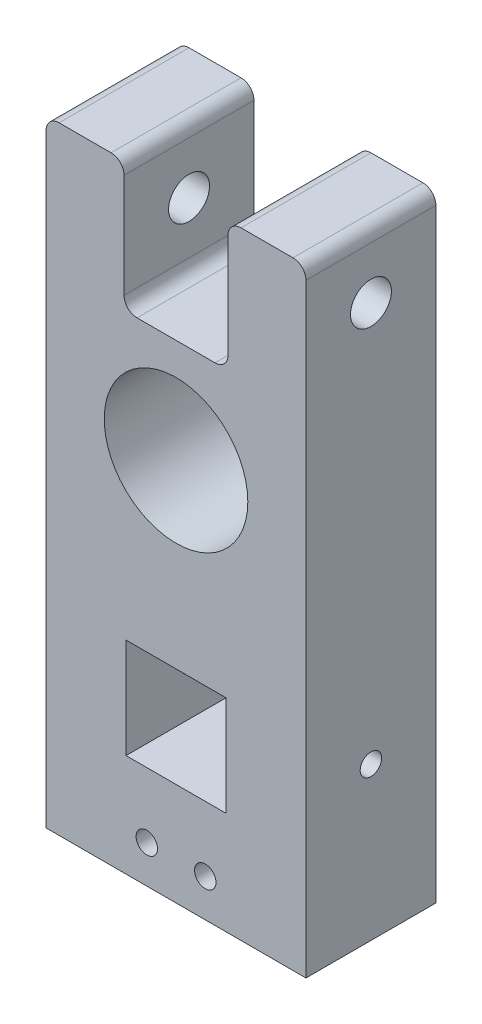
SolidWorks part; units mm, degrees
ref_plane "前视基准面" through (0, 0, 0) normal (0, 0, 1) x (1, 0, 0)
ref_plane "上视基准面" through (0, 0, 0) normal (0, 1, 0) x (1, 0, 0)
ref_plane "右视基准面" through (0, 0, 0) normal (1, 0, 0) x (0, 0, -1)
sketch "草图1" plane through (0, 0, 0) normal (0, 0, 1) x (1, 0, 0)
  line L1 (-20, -48.45) -> (20, -48.45)
  line L2 (-20, -48.45) -> (-20, 46.55)
  line L3 (-20, 46.55) -> (20, 46.55)
  line L4 (20, -48.45) -> (20, 46.55)
  line L5 (-20, -48.45) -> (20, 46.55) construction
  line L6 (-20, 46.55) -> (20, -48.45) construction
  point P0 (0, -0.95)
  dimension "D1" = 40
  dimension "D2" = 95
extrude "凸台-拉伸1" add sketch "草图1" along normal blind 20
sketch "草图2" plane through (20, 0, 0) normal (1, 0, 0) x (0, 0, -1)
  line L0 (-10, 46.55) -> (-10, -48.45) construction
  line L1 (-20, 46.55) -> (0, 46.55) construction
  line L2 (-20, -48.45) -> (0, -48.45) construction
  circle A0 centre (-10, 36.55) radius 3.15
  dimension "D1" = 6.3
  dimension "D2" = 10
extrude "切除-拉伸1" cut sketch "草图2" against normal blind 500
sketch "草图4" plane through (0, 0, 20) normal (0, 0, 1) x (1, 0, 0)
  line L0 (0, 55.2622) -> (0, -63.0108) construction
  line L1 (20, 46.55) -> (-20, 46.55) construction
  line L2 (-8, 26.55) -> (8, 26.55)
  line L3 (-8, 26.55) -> (-8, 50.8788)
  line L4 (-8, 50.8788) -> (8, 50.8788)
  line L5 (8, 26.55) -> (8, 50.8788)
  line L6 (-8, 26.55) -> (8, 50.8788) construction
  line L7 (-8, 50.8788) -> (8, 26.55) construction
  point P3 (0, 38.7144)
  dimension "D1" = 16
  dimension "D2" = 20
extrude "切除-拉伸2" cut sketch "草图4" against normal blind 500
sketch "草图5" plane through (0, 0, 20) normal (0, 0, 1) x (1, 0, 0)
  line L0 (0, 0) -> (0, 59.1338) construction
  line L1 (-8, 26.55) -> (8, 26.55) construction
  circle A0 centre (0, 10.55) radius 11.05
  dimension "D1" = 22.1
  dimension "D2" = 16
extrude "切除-拉伸3" cut sketch "草图5" against normal blind 20 contours A0
sketch "草图6" plane through (0, 0, 0) normal (0, 0, -1) x (-1, 0, 0)
  line L0 (0, 34.7599) -> (0, -43.5235) construction
  line L2 (-7.7, -32.65) -> (7.7, -32.65)
  line L3 (-7.7, -32.65) -> (-7.7, -17.25)
  line L4 (-7.7, -17.25) -> (7.7, -17.25)
  line L5 (7.7, -32.65) -> (7.7, -17.25)
  line L6 (-7.7, -32.65) -> (7.7, -17.25) construction
  line L7 (-7.7, -17.25) -> (7.7, -32.65) construction
  circle A0 centre (0, 10.55) radius 11.05 construction
  point P3 (0, -24.95)
  dimension "D1" = 35.5
  dimension "D2" = 15.4
  dimension "D3" = 15.4
extrude "切除-拉伸4" cut sketch "草图6" against normal blind 20
sketch "草图7" plane through (0, 0, 0) normal (0, 0, -1) x (-1, 0, 0)
  line L0 (0, 10.55) -> (0, -59.0903) construction
  line L1 (-38.1053, -42.65) -> (46.0439, -42.65) construction
  line L2 (-7.7, -32.65) -> (7.7, -32.65) construction
  circle A0 centre (4.5, -42.65) radius 1.65
  circle A1 centre (-4.5, -42.65) radius 1.65
  dimension "D4" = 3.3
  dimension "D5" = 3.3
  dimension "D1" = 10
  dimension "D2" = 9
  dimension "D3" = 4.5
extrude "切除-拉伸5" cut sketch "草图7" against normal blind 20
sketch "草图8" plane through (20, 0, 0) normal (1, 0, 0) x (0, 0, -1)
  line L0 (-46.0134, -24.95) -> (12.2115, -24.95) construction
  line L2 (-20, 46.55) -> (0, 46.55) construction
  line L3 (-10, -48.45) -> (-10, 22.2234) construction
  line L4 (-20, -48.45) -> (0, -48.45) construction
  circle A0 centre (-10, -24.95) radius 1.65
  dimension "D2" = 3.3
  dimension "D1" = 71.5
extrude "切除-拉伸6" cut sketch "草图8" against normal blind 50
fillet "圆角1" radius 2 6 edges at (-20, 46.55, 10) (-8, 46.55, 10) (-8, 26.55, 10) (8, 26.55, 10) (8, 46.55, 10) (20, 46.55, 10)
sketch "草图10" plane through (0, -48.45, 0) normal (0, -1, 0) x (1, 0, 0)
  line L4 (-20, 0) -> (20, 0)
  line L5 (20, 0) -> (20, 20)
  line L6 (20, 20) -> (-20, 20)
  line L7 (-20, 20) -> (-20, 0)
  line L8 (-20, 0) -> (20, 0)
  line L9 (20, 0) -> (20, 20)
  line L10 (20, 20) -> (-20, 20)
  line L11 (-20, 20) -> (-20, 0)
  dimension "D1" = 0
extrude "凸台-拉伸3" [suppressed] add sketch "草图10" along normal blind 61.5
sketch "草图11" [suppressed] plane through (0, 0, 0) normal (0, 0, -1) x (-1, 0, 0)
  line L0 (0, 0) -> (0, -116.3364) construction
  line L1 (20, -109.95) -> (-20, -109.95) construction
  line L2 (-10.2, -97.7) -> (10.2, -97.7)
  line L3 (-10.2, -97.7) -> (-10.2, -77.3)
  line L4 (-10.2, -77.3) -> (10.2, -77.3)
  line L5 (10.2, -97.7) -> (10.2, -77.3)
  line L6 (-10.2, -97.7) -> (10.2, -77.3) construction
  line L7 (-10.2, -77.3) -> (10.2, -97.7) construction
  point P3 (0, -87.5)
  dimension "D1" = 20.4
  dimension "D2" = 12.25
  dimension "D3" = 20.4
extrude "切除-拉伸7" [suppressed] cut sketch "草图11" against normal blind 61.5
sketch "草图12" [suppressed] plane through (0, 0, 0) normal (0, 0, -1) x (-1, 0, 0)
  line L0 (-45.7881, -67.3) -> (59.3814, -67.3) construction
  line L1 (0, 0) -> (0, -114.7624) construction
  line L2 (10.2, -77.3) -> (-10.2, -77.3) construction
  circle A0 centre (4.5, -67.3) radius 1.65
  circle A1 centre (-4.5, -67.3) radius 1.65
  dimension "D2" = 9
  dimension "D3" = 4.5
  dimension "D4" = 3.3
  dimension "D5" = 3.3
  dimension "D1" = 10
extrude "切除-拉伸8" [suppressed] cut sketch "草图12" against normal blind 61.5
sketch "草图13" [suppressed] plane through (-20, 0, 0) normal (-1, 0, 0) x (0, 0, 1)
  line L0 (10, 44.55) -> (10, -109.95) construction
  line L1 (20, 44.55) -> (0, 44.55) construction
  line L2 (20, -109.95) -> (0, -109.95) construction
  circle A0 centre (10, -87.5) radius 1.65
  dimension "D1" = 22.45
  dimension "D2" = 3.3
extrude "切除-拉伸9" [suppressed] cut sketch "草图13" against normal blind 61.5
fillet "圆角2" [suppressed] radius 2
